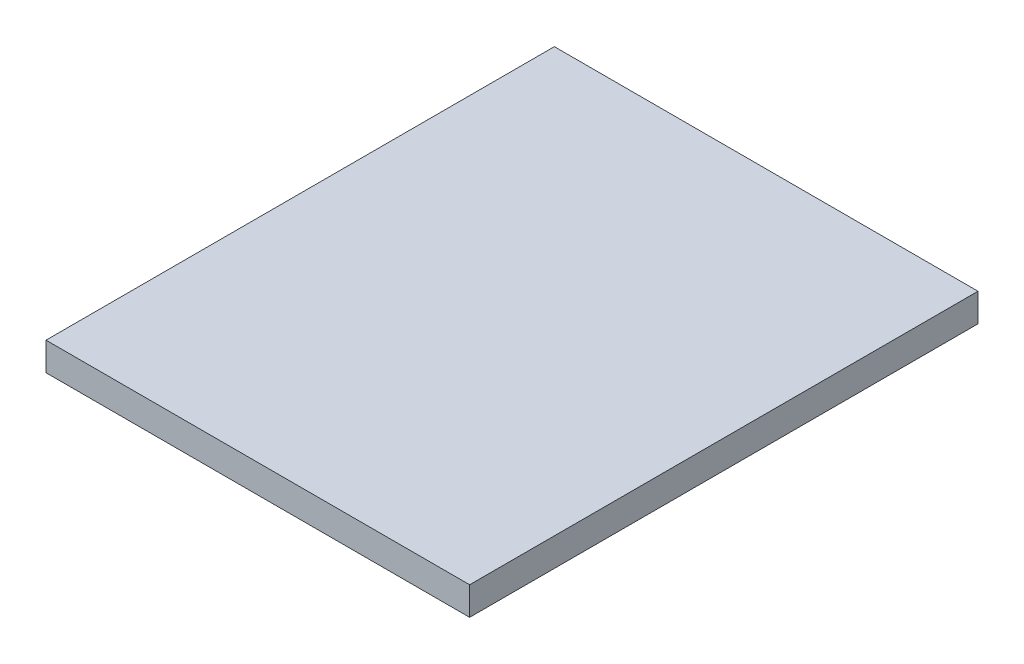
SolidWorks part; units mm, degrees
material "Plain Carbon Steel"
ref_plane "Front Plane" through (0, 0, 0) normal (0, 0, 1) x (1, 0, 0)
ref_plane "Top Plane" through (0, 0, 0) normal (0, 1, 0) x (1, 0, 0)
ref_plane "Right Plane" through (0, 0, 0) normal (1, 0, 0) x (0, 0, -1)
sketch "Sketch1" plane through (0, 0, 0) normal (0, 1, 0) x (1, 0, 0)
  line L1 (-45, -54) -> (45, -54)
  line L2 (-45, -54) -> (-45, 54)
  line L3 (-45, 54) -> (45, 54)
  line L4 (45, -54) -> (45, 54)
  line L5 (-45, -54) -> (45, 54) construction
  line L6 (-45, 54) -> (45, -54) construction
  point P0 (0, 0)
  dimension "D1" = 108
  dimension "D2" = 90
extrude "Boss-Extrude1" add sketch "Sketch1" along normal blind 6
